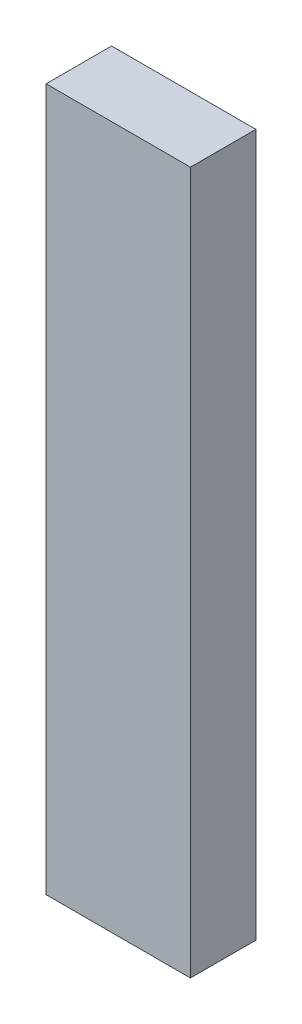
SolidWorks part; units mm, degrees
material "Pine"
ref_plane "Front Plane" through (0, 0, 0) normal (0, 0, 1) x (1, 0, 0)
ref_plane "Top Plane" through (0, 0, 0) normal (0, 1, 0) x (1, 0, 0)
ref_plane "Right Plane" through (0, 0, 0) normal (1, 0, 0) x (0, 0, -1)
sketch "Sketch1" plane through (0, 0, 0) normal (0, 1, 0) x (1, 0, 0)
  line L1 (0, 0) -> (54, 0)
  line L2 (0, 0) -> (0, 24.5)
  line L3 (0, 24.5) -> (54, 24.5)
  line L4 (54, 0) -> (54, 24.5)
  line L5 (0, 0) -> (54, 24.5) construction
  line L6 (0, 24.5) -> (54, 0) construction
  point P4 (27, 12.25)
  dimension "D1" = 24.5
  dimension "D2" = 54
extrude "Boss-Extrude1" add sketch "Sketch1" along normal blind 262.7
